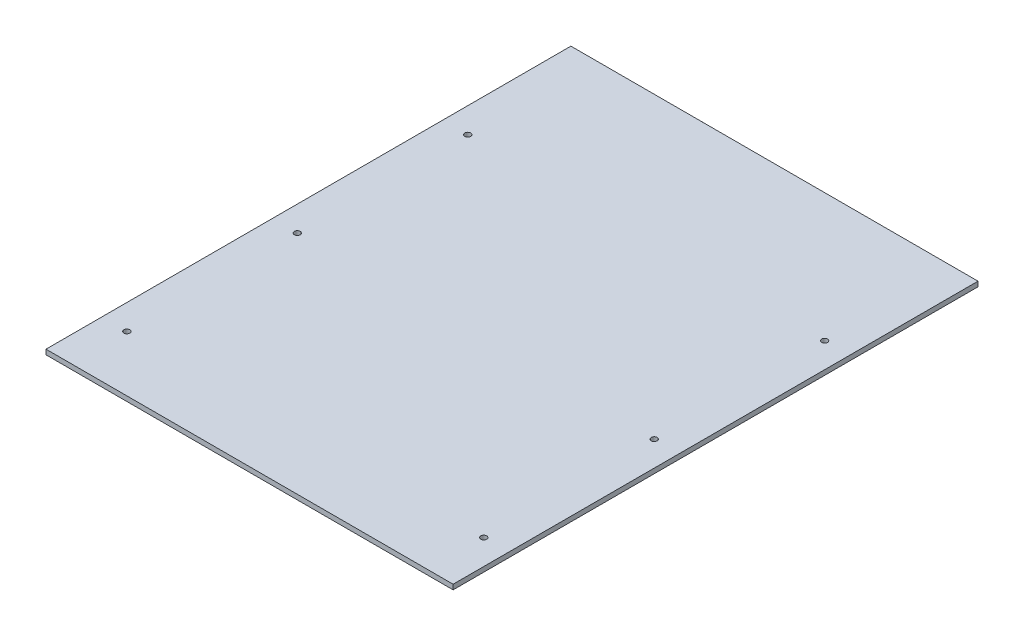
SolidWorks part; units mm, degrees
material "ABS PC"
ref_plane "Front Plane" through (0, 0, 0) normal (0, 0, 1) x (1, 0, 0)
ref_plane "Top Plane" through (0, 0, 0) normal (0, 1, 0) x (1, 0, 0)
ref_plane "Right Plane" through (0, 0, 0) normal (1, 0, 0) x (0, 0, -1)
sketch "Sketch1" plane through (0, 0, 0) normal (0, 1, 0) x (1, 0, 0)
  line L0 (231.775, 597.662) -> (231.775, 0) construction
  line L1 (0, 0) -> (463.55, 0)
  line L2 (0, 0) -> (0, 597.662)
  line L3 (0, 597.662) -> (463.55, 597.662)
  line L4 (463.55, 0) -> (463.55, 597.662)
  line L5 (28.575, 63.5) -> (28.575, 257.556) construction
  line L6 (28.575, 257.556) -> (28.575, 451.612) construction
  line L7 (434.975, 257.556) -> (434.975, 451.612) construction
  line L8 (434.975, 63.5) -> (434.975, 257.556) construction
  circle A0 centre (28.575, 63.5) radius 3.3782
  circle A1 centre (28.575, 257.556) radius 3.3782
  circle A2 centre (28.575, 451.612) radius 3.3782
  circle A3 centre (434.975, 451.612) radius 3.3782
  circle A4 centre (434.975, 257.556) radius 3.3782
  circle A5 centre (434.975, 63.5) radius 3.3782
  dimension "D3" = 6.7564
  dimension "D1" = 463.55
  dimension "D2" = 597.662
  dimension "D4" = 63.5
  dimension "D5" = 28.575
  dimension "D6" = 194.056
extrude "Boss-Extrude1" add sketch "Sketch1" along normal blind 5.588
fillet "Fillet1" [suppressed] radius 3.175
sketch "Sketch2" plane through (0, 5.588, 0) normal (0, 1, 0) x (1, 0, 0)
  line L0 (0, 581.787) -> (25.4, 581.787) construction
  line L1 (0, 597.662) -> (0, 0) construction
  line L2 (25.4, 581.787) -> (25.4, 597.662) construction
  line L3 (463.55, 597.662) -> (0, 597.662) construction
  line L4 (231.775, 597.662) -> (231.775, 0) construction
  line L5 (0, 0) -> (463.55, 0) construction
  line L6 (438.15, 581.787) -> (438.15, 597.662) construction
  line L7 (463.55, 581.787) -> (438.15, 581.787) construction
  circle A0 centre (25.4, 581.787) radius 3.3782
  circle A1 centre (438.15, 581.787) radius 3.3782
  dimension "D3" = 6.7564
  dimension "D1" = 15.875
  dimension "D2" = 25.4
extrude "Cut-Extrude1" [suppressed] cut sketch "Sketch2" against normal through all
sketch "Sketch3" plane through (0, 5.588, 0) normal (0, 1, 0) x (1, 0, 0)
  line L0 (231.775, 597.662) -> (231.775, 470.662) construction
  line L1 (463.55, 597.662) -> (0, 597.662) construction
  line L3 (114.3, 578.612) -> (349.25, 578.612) construction
  line L4 (114.3, 578.612) -> (114.3, 362.712) construction
  line L5 (114.3, 362.712) -> (349.25, 362.712) construction
  line L6 (349.25, 578.612) -> (349.25, 362.712) construction
  line L7 (114.3, 578.612) -> (349.25, 362.712) construction
  line L8 (114.3, 362.712) -> (349.25, 578.612) construction
  circle A0 centre (114.3, 578.612) radius 3.3782
  circle A1 centre (349.25, 578.612) radius 3.3782
  circle A2 centre (114.3, 362.712) radius 3.3782
  circle A3 centre (349.25, 362.712) radius 3.3782
  dimension "D3" = 6.7564
  dimension "D1" = 215.9
  dimension "D2" = 127
  dimension "D4" = 234.95
extrude "Cut-Extrude2" [suppressed] cut sketch "Sketch3" against normal through all
